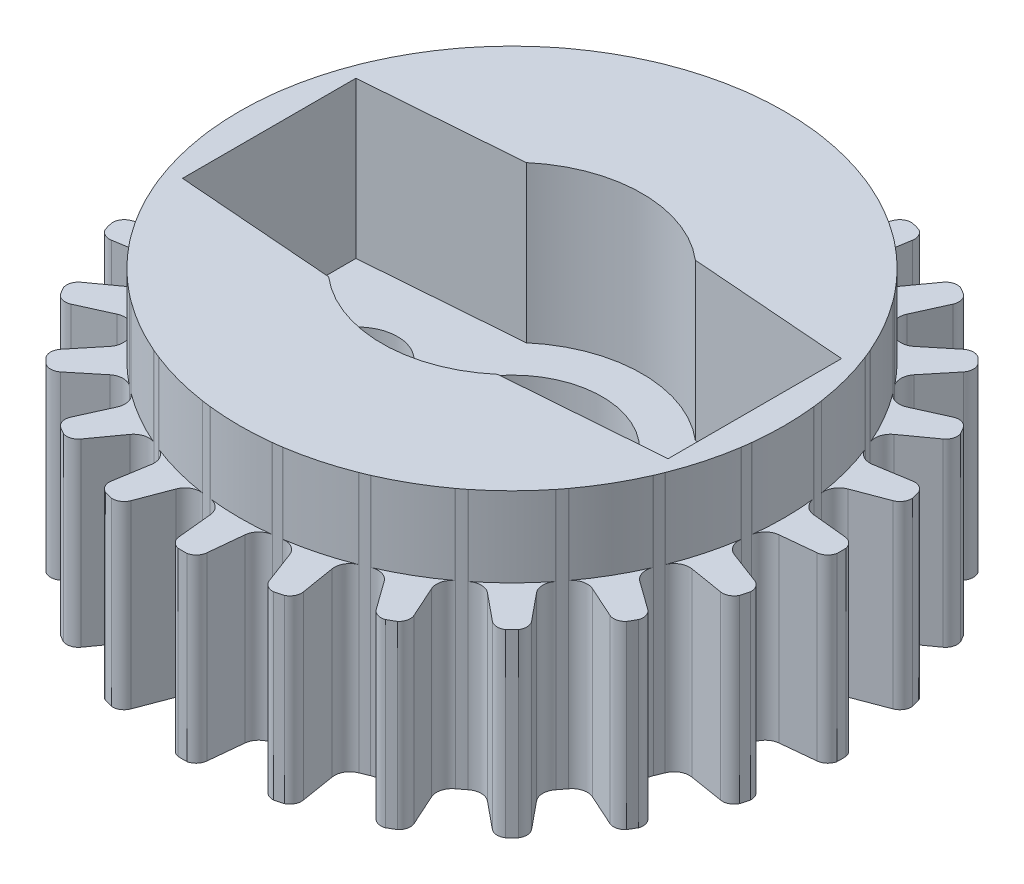
SolidWorks part; units mm, degrees
ref_plane "Front Plane" through (0, 0, 0) normal (0, 0, 1) x (1, 0, 0)
ref_plane "Top Plane" through (0, 0, 0) normal (0, 1, 0) x (1, 0, 0)
ref_plane "Right Plane" through (0, 0, 0) normal (1, 0, 0) x (0, 0, -1)
sketch "Sketch1" plane through (0, 0, 0) normal (0, 1, 0) x (1, 0, 0)
  circle A0 centre (0, 0) radius 2.6
  circle A1 centre (0, 0) radius 9.5
  dimension "D1" = 5.2
  dimension "D2" = 19
extrude "Boss-Extrude1" add sketch "Sketch1" along normal blind 7.5
sketch "Sketch2" plane through (0, 7.5, 0) normal (0, 1, 0) x (1, 0, 0)
  line L0 (0, 0) -> (0, 10.7871) construction
  line L1 (0.5, 8.2) -> (0.4, 9.2)
  line L2 (-0.5, 8.2) -> (-0.4, 9.2)
  line L3 (2.6053, 7.7912) -> (2.7675, 8.783)
  line L4 (1.6394, 8.05) -> (1.9948, 8.99)
  line L5 (4.533, 6.8514) -> (4.9464, 7.7674)
  line L6 (3.667, 7.3514) -> (4.2536, 8.1674)
  line L7 (6.1518, 5.4447) -> (6.7882, 6.2225)
  line L8 (5.4447, 6.1518) -> (6.2225, 6.7882)
  line L9 (7.3514, 3.667) -> (8.1674, 4.2536)
  line L10 (6.8514, 4.533) -> (7.7674, 4.9464)
  line L11 (8.05, 1.6394) -> (8.99, 1.9948)
  line L12 (7.7912, 2.6053) -> (8.783, 2.7675)
  line L13 (8.2, -0.5) -> (9.2, -0.4)
  line L14 (8.2, 0.5) -> (9.2, 0.4)
  line L15 (7.7912, -2.6053) -> (8.783, -2.7675)
  line L16 (8.05, -1.6394) -> (8.99, -1.9948)
  line L17 (6.8514, -4.533) -> (7.7674, -4.9464)
  line L18 (7.3514, -3.667) -> (8.1674, -4.2536)
  line L19 (5.4447, -6.1518) -> (6.2225, -6.7882)
  line L20 (6.1518, -5.4447) -> (6.7882, -6.2225)
  line L21 (3.667, -7.3514) -> (4.2536, -8.1674)
  line L22 (4.533, -6.8514) -> (4.9464, -7.7674)
  line L23 (1.6394, -8.05) -> (1.9948, -8.99)
  line L24 (2.6053, -7.7912) -> (2.7675, -8.783)
  line L25 (-0.5, -8.2) -> (-0.4, -9.2)
  line L26 (0.5, -8.2) -> (0.4, -9.2)
  line L27 (-2.6053, -7.7912) -> (-2.7675, -8.783)
  line L28 (-1.6394, -8.05) -> (-1.9948, -8.99)
  line L29 (-4.533, -6.8514) -> (-4.9464, -7.7674)
  line L30 (-3.667, -7.3514) -> (-4.2536, -8.1674)
  line L31 (-6.1518, -5.4447) -> (-6.7882, -6.2225)
  line L32 (-5.4447, -6.1518) -> (-6.2225, -6.7882)
  line L33 (-7.3514, -3.667) -> (-8.1674, -4.2536)
  line L34 (-6.8514, -4.533) -> (-7.7674, -4.9464)
  line L35 (-8.05, -1.6394) -> (-8.99, -1.9948)
  line L36 (-7.7912, -2.6053) -> (-8.783, -2.7675)
  line L37 (-8.2, 0.5) -> (-9.2, 0.4)
  line L38 (-8.2, -0.5) -> (-9.2, -0.4)
  line L39 (-7.7912, 2.6053) -> (-8.783, 2.7675)
  line L40 (-8.05, 1.6394) -> (-8.99, 1.9948)
  line L41 (-6.8514, 4.533) -> (-7.7674, 4.9464)
  line L42 (-7.3514, 3.667) -> (-8.1674, 4.2536)
  line L43 (-5.4447, 6.1518) -> (-6.2225, 6.7882)
  line L44 (-6.1518, 5.4447) -> (-6.7882, 6.2225)
  line L45 (-3.667, 7.3514) -> (-4.2536, 8.1674)
  line L46 (-4.533, 6.8514) -> (-4.9464, 7.7674)
  line L47 (-1.6394, 8.05) -> (-1.9948, 8.99)
  line L48 (-2.6053, 7.7912) -> (-2.7675, 8.783)
  arc A0 (2.8881, 7.3013) -> (3.1206, 7.205) centre (0, 0) cw
  arc A2 (0.9, 7.8) -> (1.1495, 7.7672) centre (0, 0) cw
  arc A3 (0.5, 8.2) -> (0.9, 7.8) centre (0.9444, 8.2444) ccw
  arc A4 (0, 9.5) -> (0.4, 9.2) centre (0.0622, 9.1662) cw
  arc A5 (-0.5, 8.2) -> (-0.9, 7.8) centre (-0.9444, 8.2444) cw
  arc A6 (0, 9.5) -> (-0.4, 9.2) centre (-0.0622, 9.1662) ccw
  arc A7 (2.6053, 7.7912) -> (2.8881, 7.3013) centre (3.0461, 7.7191) ccw
  arc A8 (2.4588, 9.1763) -> (2.7675, 8.783) centre (2.4324, 8.8378) cw
  arc A9 (1.6394, 8.05) -> (1.1495, 7.7672) centre (1.2216, 8.208) cw
  arc A10 (2.4588, 9.1763) -> (1.9948, 8.99) centre (2.3123, 8.87) ccw
  arc A11 (4.6794, 6.305) -> (4.879, 6.1518) centre (0, 0) cw
  arc A12 (4.533, 6.8514) -> (4.6794, 6.305) centre (4.9401, 6.6677) ccw
  arc A13 (4.75, 8.2272) -> (4.9464, 7.7674) centre (4.6369, 7.9071) cw
  arc A14 (3.667, 7.3514) -> (3.1206, 7.205) centre (3.3043, 7.6121) cw
  arc A15 (4.75, 8.2272) -> (4.2536, 8.1674) centre (4.5293, 7.9693) ccw
  arc A16 (6.1518, 4.879) -> (6.305, 4.6794) centre (0, 0) cw
  arc A17 (6.1518, 5.4447) -> (6.1518, 4.879) centre (6.4975, 5.1619) ccw
  arc A18 (6.7175, 6.7175) -> (6.7882, 6.2225) centre (6.5254, 6.4375) cw
  arc A19 (5.4447, 6.1518) -> (4.879, 6.1518) centre (5.1619, 6.4975) cw
  arc A20 (6.7175, 6.7175) -> (6.2225, 6.7882) centre (6.4375, 6.5254) ccw
  arc A21 (7.205, 3.1206) -> (7.3013, 2.8881) centre (0, 0) cw
  arc A22 (7.3514, 3.667) -> (7.205, 3.1206) centre (7.6121, 3.3043) ccw
  arc A23 (8.2272, 4.75) -> (8.1674, 4.2536) centre (7.9693, 4.5293) cw
  arc A24 (6.8514, 4.533) -> (6.305, 4.6794) centre (6.6677, 4.9401) cw
  arc A25 (8.2272, 4.75) -> (7.7674, 4.9464) centre (7.9071, 4.6369) ccw
  arc A26 (7.7672, 1.1495) -> (7.8, 0.9) centre (0, 0) cw
  arc A27 (8.05, 1.6394) -> (7.7672, 1.1495) centre (8.208, 1.2216) ccw
  arc A28 (9.1763, 2.4588) -> (8.99, 1.9948) centre (8.87, 2.3123) cw
  arc A29 (7.7912, 2.6053) -> (7.3013, 2.8881) centre (7.7191, 3.0461) cw
  arc A30 (9.1763, 2.4588) -> (8.783, 2.7675) centre (8.8378, 2.4324) ccw
  arc A31 (7.8, -0.9) -> (7.7672, -1.1495) centre (0, 0) cw
  arc A32 (8.2, -0.5) -> (7.8, -0.9) centre (8.2444, -0.9444) ccw
  arc A33 (9.5, 0) -> (9.2, -0.4) centre (9.1662, -0.0622) cw
  arc A34 (8.2, 0.5) -> (7.8, 0.9) centre (8.2444, 0.9444) cw
  arc A35 (9.5, 0) -> (9.2, 0.4) centre (9.1662, 0.0622) ccw
  arc A36 (7.3013, -2.8881) -> (7.205, -3.1206) centre (0, 0) cw
  arc A37 (7.7912, -2.6053) -> (7.3013, -2.8881) centre (7.7191, -3.0461) ccw
  arc A38 (9.1763, -2.4588) -> (8.783, -2.7675) centre (8.8378, -2.4324) cw
  arc A39 (8.05, -1.6394) -> (7.7672, -1.1495) centre (8.208, -1.2216) cw
  arc A40 (9.1763, -2.4588) -> (8.99, -1.9948) centre (8.87, -2.3123) ccw
  arc A41 (6.305, -4.6794) -> (6.1518, -4.879) centre (0, 0) cw
  arc A42 (6.8514, -4.533) -> (6.305, -4.6794) centre (6.6677, -4.9401) ccw
  arc A43 (8.2272, -4.75) -> (7.7674, -4.9464) centre (7.9071, -4.6369) cw
  arc A44 (7.3514, -3.667) -> (7.205, -3.1206) centre (7.6121, -3.3043) cw
  arc A45 (8.2272, -4.75) -> (8.1674, -4.2536) centre (7.9693, -4.5293) ccw
  arc A46 (4.879, -6.1518) -> (4.6794, -6.305) centre (0, 0) cw
  arc A47 (5.4447, -6.1518) -> (4.879, -6.1518) centre (5.1619, -6.4975) ccw
  arc A48 (6.7175, -6.7175) -> (6.2225, -6.7882) centre (6.4375, -6.5254) cw
  arc A49 (6.1518, -5.4447) -> (6.1518, -4.879) centre (6.4975, -5.1619) cw
  arc A50 (6.7175, -6.7175) -> (6.7882, -6.2225) centre (6.5254, -6.4375) ccw
  arc A51 (3.1206, -7.205) -> (2.8881, -7.3013) centre (0, 0) cw
  arc A52 (3.667, -7.3514) -> (3.1206, -7.205) centre (3.3043, -7.6121) ccw
  arc A53 (4.75, -8.2272) -> (4.2536, -8.1674) centre (4.5293, -7.9693) cw
  arc A54 (4.533, -6.8514) -> (4.6794, -6.305) centre (4.9401, -6.6677) cw
  arc A55 (4.75, -8.2272) -> (4.9464, -7.7674) centre (4.6369, -7.9071) ccw
  arc A56 (1.1495, -7.7672) -> (0.9, -7.8) centre (0, 0) cw
  arc A57 (1.6394, -8.05) -> (1.1495, -7.7672) centre (1.2216, -8.208) ccw
  arc A58 (2.4588, -9.1763) -> (1.9948, -8.99) centre (2.3123, -8.87) cw
  arc A59 (2.6053, -7.7912) -> (2.8881, -7.3013) centre (3.0461, -7.7191) cw
  arc A60 (2.4588, -9.1763) -> (2.7675, -8.783) centre (2.4324, -8.8378) ccw
  arc A61 (-0.9, -7.8) -> (-1.1495, -7.7672) centre (0, 0) cw
  arc A62 (-0.5, -8.2) -> (-0.9, -7.8) centre (-0.9444, -8.2444) ccw
  arc A63 (0, -9.5) -> (-0.4, -9.2) centre (-0.0622, -9.1662) cw
  arc A64 (0.5, -8.2) -> (0.9, -7.8) centre (0.9444, -8.2444) cw
  arc A65 (0, -9.5) -> (0.4, -9.2) centre (0.0622, -9.1662) ccw
  arc A66 (-2.8881, -7.3013) -> (-3.1206, -7.205) centre (0, 0) cw
  arc A67 (-2.6053, -7.7912) -> (-2.8881, -7.3013) centre (-3.0461, -7.7191) ccw
  arc A68 (-2.4588, -9.1763) -> (-2.7675, -8.783) centre (-2.4324, -8.8378) cw
  arc A69 (-1.6394, -8.05) -> (-1.1495, -7.7672) centre (-1.2216, -8.208) cw
  arc A70 (-2.4588, -9.1763) -> (-1.9948, -8.99) centre (-2.3123, -8.87) ccw
  arc A71 (-4.6794, -6.305) -> (-4.879, -6.1518) centre (0, 0) cw
  arc A72 (-4.533, -6.8514) -> (-4.6794, -6.305) centre (-4.9401, -6.6677) ccw
  arc A73 (-4.75, -8.2272) -> (-4.9464, -7.7674) centre (-4.6369, -7.9071) cw
  arc A74 (-3.667, -7.3514) -> (-3.1206, -7.205) centre (-3.3043, -7.6121) cw
  arc A75 (-4.75, -8.2272) -> (-4.2536, -8.1674) centre (-4.5293, -7.9693) ccw
  arc A76 (-6.1518, -4.879) -> (-6.305, -4.6794) centre (0, 0) cw
  arc A77 (-6.1518, -5.4447) -> (-6.1518, -4.879) centre (-6.4975, -5.1619) ccw
  arc A78 (-6.7175, -6.7175) -> (-6.7882, -6.2225) centre (-6.5254, -6.4375) cw
  arc A79 (-5.4447, -6.1518) -> (-4.879, -6.1518) centre (-5.1619, -6.4975) cw
  arc A80 (-6.7175, -6.7175) -> (-6.2225, -6.7882) centre (-6.4375, -6.5254) ccw
  arc A81 (-7.205, -3.1206) -> (-7.3013, -2.8881) centre (0, 0) cw
  arc A82 (-7.3514, -3.667) -> (-7.205, -3.1206) centre (-7.6121, -3.3043) ccw
  arc A83 (-8.2272, -4.75) -> (-8.1674, -4.2536) centre (-7.9693, -4.5293) cw
  arc A84 (-6.8514, -4.533) -> (-6.305, -4.6794) centre (-6.6677, -4.9401) cw
  arc A85 (-8.2272, -4.75) -> (-7.7674, -4.9464) centre (-7.9071, -4.6369) ccw
  arc A86 (-7.7672, -1.1495) -> (-7.8, -0.9) centre (0, 0) cw
  arc A87 (-8.05, -1.6394) -> (-7.7672, -1.1495) centre (-8.208, -1.2216) ccw
  arc A88 (-9.1763, -2.4588) -> (-8.99, -1.9948) centre (-8.87, -2.3123) cw
  arc A89 (-7.7912, -2.6053) -> (-7.3013, -2.8881) centre (-7.7191, -3.0461) cw
  arc A90 (-9.1763, -2.4588) -> (-8.783, -2.7675) centre (-8.8378, -2.4324) ccw
  arc A91 (-7.8, 0.9) -> (-7.7672, 1.1495) centre (0, 0) cw
  arc A92 (-8.2, 0.5) -> (-7.8, 0.9) centre (-8.2444, 0.9444) ccw
  arc A93 (-9.5, 0) -> (-9.2, 0.4) centre (-9.1662, 0.0622) cw
  arc A94 (-8.2, -0.5) -> (-7.8, -0.9) centre (-8.2444, -0.9444) cw
  arc A95 (-9.5, 0) -> (-9.2, -0.4) centre (-9.1662, -0.0622) ccw
  arc A96 (-7.3013, 2.8881) -> (-7.205, 3.1206) centre (0, 0) cw
  arc A97 (-7.7912, 2.6053) -> (-7.3013, 2.8881) centre (-7.7191, 3.0461) ccw
  arc A98 (-9.1763, 2.4588) -> (-8.783, 2.7675) centre (-8.8378, 2.4324) cw
  arc A99 (-8.05, 1.6394) -> (-7.7672, 1.1495) centre (-8.208, 1.2216) cw
  arc A100 (-9.1763, 2.4588) -> (-8.99, 1.9948) centre (-8.87, 2.3123) ccw
  arc A101 (-6.305, 4.6794) -> (-6.1518, 4.879) centre (0, 0) cw
  arc A102 (-6.8514, 4.533) -> (-6.305, 4.6794) centre (-6.6677, 4.9401) ccw
  arc A103 (-8.2272, 4.75) -> (-7.7674, 4.9464) centre (-7.9071, 4.6369) cw
  arc A104 (-7.3514, 3.667) -> (-7.205, 3.1206) centre (-7.6121, 3.3043) cw
  arc A105 (-8.2272, 4.75) -> (-8.1674, 4.2536) centre (-7.9693, 4.5293) ccw
  arc A106 (-4.879, 6.1518) -> (-4.6794, 6.305) centre (0, 0) cw
  arc A107 (-5.4447, 6.1518) -> (-4.879, 6.1518) centre (-5.1619, 6.4975) ccw
  arc A108 (-6.7175, 6.7175) -> (-6.2225, 6.7882) centre (-6.4375, 6.5254) cw
  arc A109 (-6.1518, 5.4447) -> (-6.1518, 4.879) centre (-6.4975, 5.1619) cw
  arc A110 (-6.7175, 6.7175) -> (-6.7882, 6.2225) centre (-6.5254, 6.4375) ccw
  arc A111 (-3.1206, 7.205) -> (-2.8881, 7.3013) centre (0, 0) cw
  arc A112 (-3.667, 7.3514) -> (-3.1206, 7.205) centre (-3.3043, 7.6121) ccw
  arc A113 (-4.75, 8.2272) -> (-4.2536, 8.1674) centre (-4.5293, 7.9693) cw
  arc A114 (-4.533, 6.8514) -> (-4.6794, 6.305) centre (-4.9401, 6.6677) cw
  arc A115 (-4.75, 8.2272) -> (-4.9464, 7.7674) centre (-4.6369, 7.9071) ccw
  arc A116 (-1.1495, 7.7672) -> (-0.9, 7.8) centre (0, 0) cw
  arc A117 (-1.6394, 8.05) -> (-1.1495, 7.7672) centre (-1.2216, 8.208) ccw
  arc A118 (-2.4588, 9.1763) -> (-1.9948, 8.99) centre (-2.3123, 8.87) cw
  arc A119 (-2.6053, 7.7912) -> (-2.8881, 7.3013) centre (-3.0461, 7.7191) cw
  arc A120 (-2.4588, 9.1763) -> (-2.7675, 8.783) centre (-2.4324, 8.8378) ccw
  circle A121 centre (0, 0) radius 9.5 construction
  circle A132 centre (0, 0) radius 11.1781
  point P296 (0, 0)
  dimension "D7" = 24
  dimension "D1" = 0.4
  dimension "D2" = 0.1
  dimension "D3" = 1
  dimension "D4" = 0.3
  dimension "D5" = 0.4
  dimension "D6" = 0.4
extrude "Cut-Extrude1" cut sketch "Sketch2" against normal up to next
sketch "Sketch3" plane through (0, 7.5, 0) normal (0, 1, 0) x (1, 0, 0)
  circle A0 centre (0, 0) radius 2.6 construction
  circle A1 centre (0, 0) radius 2.6
  circle A2 centre (0, 0) radius 0.875
  dimension "D1" = 1.75
extrude "Boss-Extrude2" add sketch "Sketch3" against normal blind 3.25
sketch "Sketch4" plane through (0, 7.5, 0) normal (0, 1, 0) x (1, 0, 0)
  line L0 (-7, 2.5) -> (-2.4372, 2.85)
  line L1 (-7, -2.5) -> (-2.4372, -2.85)
  line L2 (-7, 2.5) -> (-7, -2.5)
  line L3 (0, 3.75) -> (0, -3.75) construction
  line L4 (7, 2.5) -> (7, -2.5)
  line L5 (7, -2.5) -> (2.4372, -2.85)
  line L6 (7, 2.5) -> (2.4372, 2.85)
  arc A2 (2.4372, 2.85) -> (-2.4372, 2.85) centre (0, 0) ccw
  arc A3 (-2.4372, -2.85) -> (2.4372, -2.85) centre (0, 0) ccw
  dimension "D2" = 3.75
  dimension "D3" = 5.7
  dimension "D4" = 7
  dimension "D5" = 7
  dimension "D6" = 5
extrude "Cut-Extrude2" cut sketch "Sketch4" against normal blind 4.5
sketch "Sketch5" plane through (0, 3, 0) normal (0, 1, 0) x (1, 0, 0)
  circle A0 centre (-4.45, 0) radius 1.15
  circle A1 centre (4.45, 0) radius 1.15
  dimension "D3" = 2.3
  dimension "D1" = 4.45
  dimension "D2" = 4.45
extrude "Cut-Extrude3" cut sketch "Sketch5" against normal up to next
sketch "Sketch6" plane through (0, 7.5, 0) normal (0, 1, 0) x (1, 0, 0)
  circle A0 centre (0, 0) radius 10.6803
  circle A1 centre (0, 0) radius 7.8518
extrude "Cut-Extrude4" cut sketch "Sketch6" against normal blind 2.3
equation "\"D2@Sketch4\"=\"D1@Sketch4\"/2"
equation "\"D5@Sketch4\"=\"D4@Sketch4\""
equation "\"D2@Sketch5\"=\"D1@Sketch5\""
